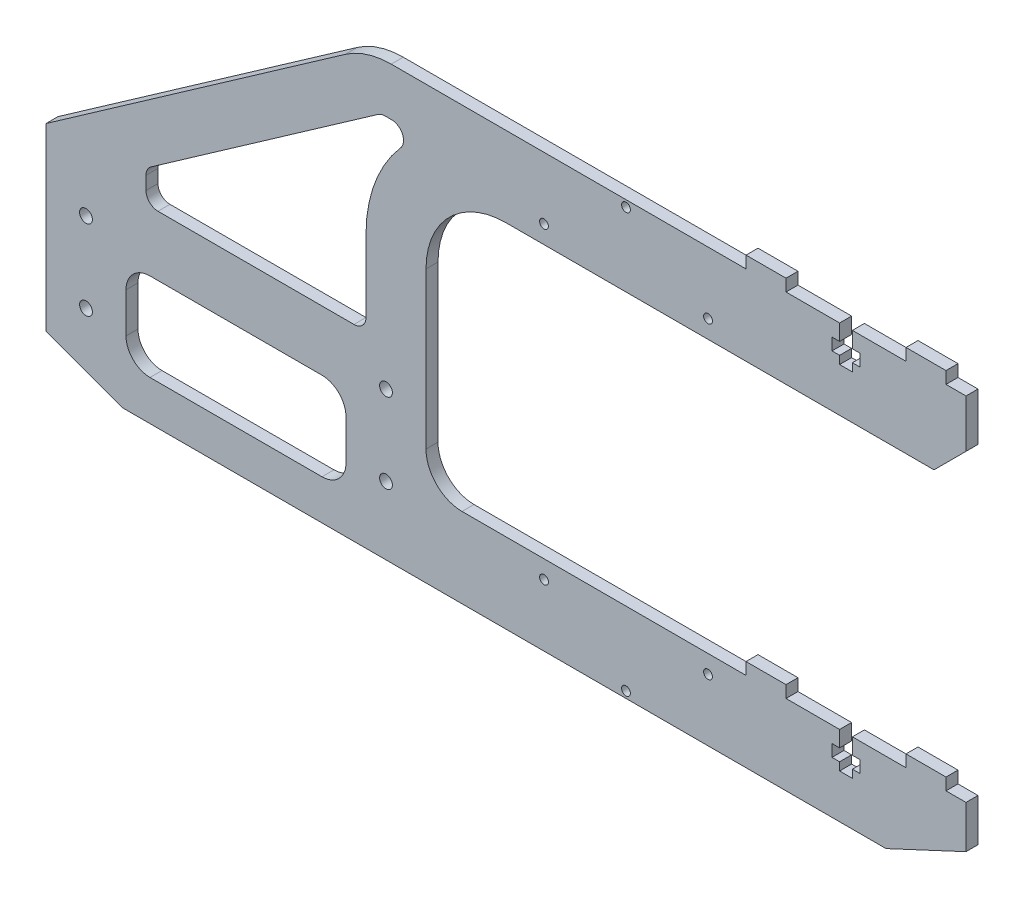
SolidWorks part; units mm, degrees
material "Thornel Mat VMA"
ref_plane "前视基准面" through (0, 0, 0) normal (0, 0, 1) x (1, 0, 0)
ref_plane "上视基准面" through (0, 0, 0) normal (0, 1, 0) x (1, 0, 0)
ref_plane "右视基准面" through (0, 0, 0) normal (1, 0, 0) x (0, 0, -1)
sketch "草图1" plane through (0, 0, 0) normal (0, 0, 1) x (1, 0, 0)
  line L0 (0, 109.7428) -> (0, -92.3405) construction
  line L1 (-111.3443, 0) -> (156.3674, 0) construction
  line L2 (-47.5, -22.5) -> (-47.5, 22.5)
  line L3 (-47.5, 22.5) -> (32.5, 78.5166)
  line L5 (32.5, 78.5166) -> (182.5, 78.5166)
  line L6 (182.5, 78.5166) -> (182.5, -29.4834) construction
  line L7 (182.5, -29.4834) -> (-28.3133, -29.4834)
  line L9 (-28.3133, -29.4834) -> (-47.5, -22.5)
  line L12 (47.5, -9.4834) -> (182.5, -9.4834)
  line L14 (47.5, 58.5166) -> (182.5, 58.5166)
  line L15 (182.5, 58.5166) -> (182.5, 78.5166)
  line L16 (182.5, -9.4834) -> (182.5, -29.4834)
  line L17 (47.5, 58.5166) -> (47.5, -9.4834)
  circle A0 centre (-37.5, 7.5) radius 1.6
  circle A1 centre (-37.5, -12.5) radius 1.6
  circle A2 centre (37.5, 7.5) radius 1.6
  circle A3 centre (37.5, -12.5) radius 1.6
  dimension "D1" = 75
  dimension "D2" = 20
  dimension "D3" = 3.2
  dimension "D14" = 10
  dimension "D4" = 10
  dimension "D5" = 15
  dimension "D6" = 10
  dimension "D7" = 35
  dimension "D8" = 45
  dimension "D9" = 20
  dimension "D10" = 145
  dimension "D11" = 68
  dimension "D12" = 20
  dimension "D13" = 20
extrude "凸台-拉伸1" add sketch "草图1" along normal blind 3
sketch "草图4" plane through (0, 0, 3) normal (0, 0, 1) x (1, 0, 0)
  line L0 (182.5, 78.5166) -> (32.5, 78.5166) construction
  line L1 (127.5, 78.5166) -> (137.5, 78.5166)
  line L2 (127.5, 78.5166) -> (127.5, 81.5166)
  line L3 (127.5, 81.5166) -> (137.5, 81.5166)
  line L4 (137.5, 78.5166) -> (137.5, 81.5166)
  line L5 (152.5, 78.5166) -> (152.5, 50.8127) construction
  line L6 (177.5, 78.5166) -> (167.5, 78.5166)
  line L7 (177.5, 78.5166) -> (177.5, 81.5166)
  line L8 (177.5, 81.5166) -> (167.5, 81.5166)
  line L9 (167.5, 78.5166) -> (167.5, 81.5166)
  line L10 (182.5, 58.5166) -> (182.5, 78.5166) construction
  line L11 (182.5, -9.4834) -> (47.5, -9.4834) construction
  line L12 (127.5, -9.4834) -> (137.5, -9.4834)
  line L13 (127.5, -9.4834) -> (127.5, -6.4834)
  line L14 (127.5, -6.4834) -> (137.5, -6.4834)
  line L15 (137.5, -9.4834) -> (137.5, -6.4834)
  line L17 (167.5, -9.4834) -> (177.5, -9.4834)
  line L18 (167.5, -9.4834) -> (167.5, -6.4834)
  line L19 (167.5, -6.4834) -> (177.5, -6.4834)
  line L20 (177.5, -9.4834) -> (177.5, -6.4834)
  point P14 (132.5, 81.5166)
  point P15 (172.5, 81.5166)
  dimension "D1" = 40
  dimension "D2" = 10
  dimension "D3" = 3
  dimension "D4" = 30
extrude "凸台-拉伸2" add sketch "草图4" against normal up to surface (3 mm away) up to face at (39.1, 7.5, 0)
sketch "草图5" plane through (0, 0, 3) normal (0, 0, 1) x (1, 0, 0)
  line L0 (152.5, 78.5166) -> (152.5, -9.4834) construction
  line L1 (167.5, 78.5166) -> (137.5, 78.5166) construction
  line L2 (167.5, -9.4834) -> (137.5, -9.4834) construction
  line L3 (177.5, 81.5166) -> (167.5, 81.5166) construction
  line L4 (150.9, 78.5166) -> (154.1, 78.5166)
  line L5 (150.9, 78.5166) -> (150.9, 74.5166)
  line L6 (150.9, 69.5166) -> (154.1, 69.5166)
  line L7 (154.1, 78.5166) -> (154.1, 74.5166)
  line L8 (149, 74.5166) -> (150.9, 74.5166)
  line L9 (149, 74.5166) -> (149, 71.5166)
  line L10 (149, 71.5166) -> (150.9, 71.5166)
  line L11 (156, 74.5166) -> (156, 71.5166)
  line L12 (154.1, 74.5166) -> (156, 74.5166)
  line L13 (150.9, 71.5166) -> (150.9, 69.5166)
  line L14 (154.1, 71.5166) -> (154.1, 69.5166)
  line L15 (154.1, 71.5166) -> (156, 71.5166)
  line L16 (177.5, -6.4834) -> (167.5, -6.4834) construction
  line L17 (150.9, -9.4834) -> (154.1, -9.4834)
  line L18 (150.9, -9.4834) -> (150.9, -13.4834)
  line L19 (150.9, -18.4834) -> (154.1, -18.4834)
  line L20 (154.1, -9.4834) -> (154.1, -13.4834)
  line L21 (149, -13.4834) -> (150.9, -13.4834)
  line L22 (149, -13.4834) -> (149, -16.4834)
  line L23 (149, -16.4834) -> (150.9, -16.4834)
  line L24 (156, -13.4834) -> (156, -16.4834)
  line L25 (154.1, -13.4834) -> (156, -13.4834)
  line L26 (154.1, -16.4834) -> (154.1, -18.4834)
  line L27 (154.1, -16.4834) -> (156, -16.4834)
  line L28 (150.9, -16.4834) -> (150.9, -18.4834)
  line L29 (97.5, -27.8334) -> (97.5, 83.9455) construction
  line L30 (127.5, -9.4834) -> (47.5, -9.4834) construction
  line L31 (47.5, 58.5166) -> (182.5, 58.5166) construction
  circle A0 centre (77, -13.9834) radius 1.1
  circle A1 centre (118, -13.9834) radius 1.1
  circle A2 centre (97.5, -27.8334) radius 1.1
  circle A3 centre (77, 63.0166) radius 1.1
  circle A4 centre (118, 63.0166) radius 1.1
  circle A5 centre (97.5, 76.8666) radius 1.1
  dimension "D11" = 2.2
  dimension "D12" = 41
  dimension "D13" = 13.85
  dimension "D14" = 4.5
  dimension "D15" = 55
  dimension "D16" = 13.85
  dimension "D17" = 41
  dimension "D18" = 4.5
  dimension "D1" = 12
  dimension "D2" = 3
  dimension "D3" = 7
  dimension "D4" = 3.2
  dimension "D5" = 4
  dimension "D6" = 3.2
  dimension "D7" = 7
  dimension "D8" = 12
  dimension "D9" = 3
  dimension "D10" = 4
extrude "切除-拉伸1" cut sketch "草图5" against normal through all
fillet "圆角1" radius 20 1 edges at (47.5, 58.5166, 1.5)
fillet "圆角2" radius 9 1 edges at (47.5, -9.4834, 1.5)
sketch "草图6" plane through (0, 0, 3) normal (0, 0, 1) x (1, 0, 0)
  line L0 (-22.5, 25.3559) -> (36.2836, 66.5166)
  line L1 (36.2836, 66.5166) -> (46.5, 66.5166)
  line L3 (32.5, 17.5) -> (-22.5, 17.5)
  line L4 (-22.5, 17.5) -> (-22.5, 25.3559)
  line L5 (32.5, 78.5166) -> (-47.5, 22.5) construction
  line L9 (32.5, 17.5) -> (32.5, 38.5166)
  line L10 (47.5, -0.4834) -> (47.5, 38.5166) construction
  line L11 (-47.5, 22.5) -> (-47.5, -22.5) construction
  line L12 (-28.3133, -29.4834) -> (182.5, -29.4834) construction
  line L13 (-27.5, 2.5) -> (27.5, 2.5)
  line L14 (-27.5, 2.5) -> (-27.5, -19.4834)
  line L15 (-27.5, -19.4834) -> (27.5, -19.4834)
  line L16 (27.5, 2.5) -> (27.5, -19.4834)
  line L17 (-27.5, 2.5) -> (27.5, -19.4834) construction
  line L18 (-27.5, -19.4834) -> (27.5, 2.5) construction
  line L19 (127.5, 78.5166) -> (32.5, 78.5166) construction
  arc A0 (46.5, 66.5166) -> (32.5, 38.5166) centre (67.5, 38.5166) ccw
  arc A1 (67.5, 58.5166) -> (47.5, 38.5166) centre (67.5, 38.5166) ccw construction
  circle A2 centre (37.5, 7.5) radius 1.6 construction
  circle A3 centre (-37.5, -12.5) radius 1.6 construction
  circle A4 centre (37.5, -12.5) radius 1.6 construction
  point P8 (0, -8.4917)
  dimension "D2" = 15
  dimension "D1" = 12
  dimension "D3" = 12
  dimension "D4" = 10
  dimension "D5" = 15
  dimension "D6" = 25
  dimension "D8" = 15
  dimension "D9" = 10
  dimension "D10" = 10
  dimension "D11" = 10
extrude "切除-拉伸2" cut sketch "草图6" against normal through all
fillet "圆角3" radius 6 4 edges at (-27.5, -19.4834, 1.5) (27.5, -19.4834, 1.5) (27.5, 2.5, 1.5) (-27.5, 2.5, 1.5)
fillet "圆角4" radius 3 5 edges at (36.2836, 66.5166, 1.5) (32.5, 17.5, 1.5) (-22.5, 25.3559, 1.5) (-22.5, 17.5, 1.5) (46.5, 66.5166, 1.5)
fillet "圆角5" radius 20 1 edges at (32.5, 78.5166, 1.5)
chamfer "倒角1" distance 8 angle 45 1 edges at (182.5, 58.5166, 1.5)
chamfer "倒角3" distance 20 angle 25 1 edges at (182.5, -29.4834, 1.5)
